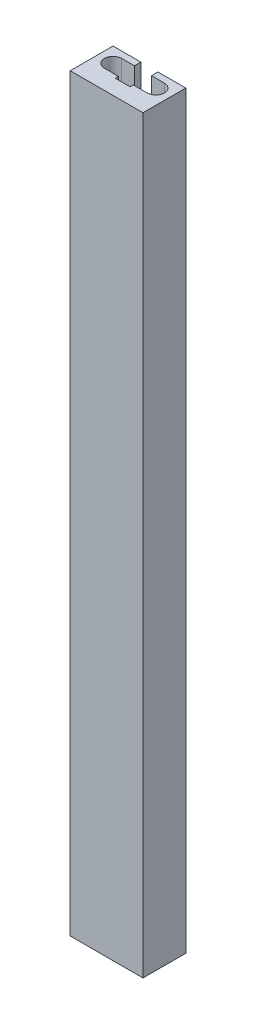
SolidWorks part; units mm, degrees
ref_plane "Спереди" through (0, 0, 0) normal (0, 0, 1) x (1, 0, 0)
ref_plane "Сверху" through (0, 0, 0) normal (0, 1, 0) x (1, 0, 0)
ref_plane "Справа" through (0, 0, 0) normal (1, 0, 0) x (0, 0, -1)
other "Configuration Table"
sketch "Sketch1" plane through (0, 0, 0) normal (0, 0, 1) x (1, 0, 0)
  line L1 (-17, -175) -> (17, -175)
  line L2 (-17, -175) -> (-17, 175)
  line L3 (-17, 175) -> (17, 175)
  line L4 (17, -175) -> (17, 175)
  line L5 (-17, -175) -> (17, 175) construction
  line L6 (-17, 175) -> (17, -175) construction
  point P0 (0, 0)
  dimension "D1" = 34
  dimension "D2" = 350
extrude "Boss-Extrude1" add sketch "Sketch1" along normal blind 20
sketch "Sketch2" plane through (0, 175, 0) normal (0, 1, 0) x (1, 0, 0)
  line L0 (-22.7362, -7) -> (23.9934, -7) construction
  line L1 (-10, -3) -> (-4, -3)
  line L2 (-4, -3) -> (-4, 0)
  line L3 (17, 0) -> (-17, 0) construction
  line L4 (-4, 0) -> (4, 0)
  line L5 (4, 0) -> (4, -3)
  line L6 (4, -3) -> (10, -3)
  line L7 (10, -11) -> (3.5, -11)
  line L8 (0, 5.3098) -> (0, -15.121) construction
  line L11 (-3.5, -11) -> (-3.5, -12.5)
  line L12 (-3.5, -12.5) -> (3.5, -12.5)
  line L13 (3.5, -12.5) -> (3.5, -11)
  line L14 (-3.5, -11) -> (-10, -11)
  arc A0 (10, -3) -> (10, -11) centre (10, -7) cw
  arc A1 (-10, -11) -> (-10, -3) centre (-10, -7) cw
  point P17 (0, 0)
  point P24 (3.5389, -11)
  dimension "D1" = 4
  dimension "D2" = 3
  dimension "D7" = 28
  dimension "D3" = 7
  dimension "D4" = 8
  dimension "D5" = 1.5
extrude "Cut-Extrude1" cut sketch "Sketch2" against normal offset from surface (330 mm away) 20 up to face at (0, -175, 10)
